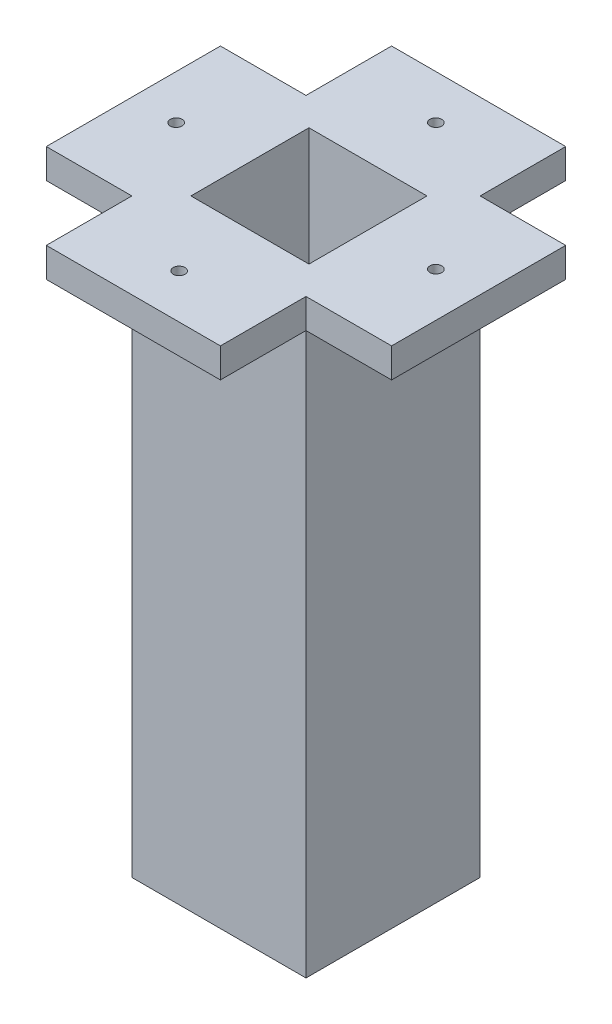
SolidWorks part; units mm, degrees
ref_plane "Plan de face" through (0, 0, 0) normal (0, 0, 1) x (1, 0, 0)
ref_plane "Plan de dessus" through (0, 0, 0) normal (0, 1, 0) x (1, 0, 0)
ref_plane "Plan de droite" through (0, 0, 0) normal (1, 0, 0) x (0, 0, -1)
sketch "Esquisse1" plane through (0, 0, 0) normal (0, 1, 0) x (1, 0, 0)
  line L1 (0, 0) -> (59, 0)
  line L2 (0, 0) -> (0, 59)
  line L3 (0, 59) -> (59, 59)
  line L4 (59, 0) -> (59, 59)
extrude "Boss.-Extru.1" add sketch "Esquisse1" along normal blind 200 contours L2 L1 L4 L3
sketch "Esquisse2" plane through (0, 200, 0) normal (0, 1, 0) x (1, 0, 0)
  line L1 (10, 50) -> (50, 50)
  line L2 (10, 50) -> (10, 10)
  line L3 (10, 10) -> (50, 10)
  line L4 (50, 50) -> (50, 10)
extrude "Enlèv. mat.-Extru.1" cut sketch "Esquisse2" against normal blind 250 contours L2 L1 L4 L3
sketch "Esquisse3" plane through (0, 0, 0) normal (1, 0, 0) x (0, 0, -1)
  line L5 (39, 120) -> (20, 120)
  line L6 (39, 120) -> (39, 79)
  line L7 (39, 79) -> (20, 79)
  line L8 (20, 120) -> (20, 79)
  line L13 (0, 200) -> (59, 200) construction
  line L14 (59, 200) -> (59, 0) construction
  line L15 (0, 71.0556) -> (0, -71.0556) construction
  dimension "D1" = 80
  dimension "D2" = 20
  dimension "D3" = 121
  dimension "D4" = 20
extrude "Enlèv. mat.-Extru.7" cut sketch "Esquisse3" along normal blind 10
sketch "Esquisse6" plane through (0, 0, 0) normal (-1, 0, 0) x (0, 0, 1)
  line L0 (-39, 120) -> (-20, 120) construction
  line L1 (-20, 120) -> (-20, 79) construction
  line L2 (-39, 79) -> (-39, 120) construction
  line L3 (-20, 79) -> (-39, 79) construction
  circle A0 centre (-33.5, 123.5) radius 2
  circle A1 centre (-25.5, 123.5) radius 2
  circle A2 centre (-33.5, 75.5) radius 2
  circle A3 centre (-25.5, 75.5) radius 2
  dimension "D1" = 3.5
  dimension "D2" = 4
  dimension "D4" = 4
  dimension "D7" = 5.5
  dimension "D11" = 4
  dimension "D12" = 4
  dimension "D3" = 5.5
  dimension "D5" = 3.5
  dimension "D6" = 5.5
  dimension "D8" = 5.5
  dimension "D9" = 3.5
  dimension "D10" = 3.5
extrude "Enlèv. mat.-Extru.8" cut sketch "Esquisse6" against normal blind 10
sketch "Esquisse14" plane through (0, 200, 0) normal (0, 1, 0) x (1, 0, 0)
  line L0 (0, -46.4511) -> (0, 46.4511) construction
  line L1 (59, 59) -> (0, 59)
  line L2 (59, 59) -> (59, 88)
  line L3 (59, 88) -> (0, 88)
  line L4 (0, 59) -> (0, 88)
  line L5 (-71.0556, 0) -> (71.0556, 0) construction
  line L6 (59, 59) -> (88, 59)
  line L7 (59, 59) -> (59, 0)
  line L8 (59, 0) -> (88, 0)
  line L9 (88, 59) -> (88, 0)
  line L11 (0, 59) -> (-29, 59)
  line L12 (0, 59) -> (0, 0)
  line L13 (0, 0) -> (-29, 0)
  line L14 (-29, 59) -> (-29, 0)
  line L15 (0, 0) -> (59, 0)
  line L16 (0, 0) -> (0, -29)
  line L17 (0, -29) -> (59, -29)
  line L18 (59, 0) -> (59, -29)
  line M9 (59, 59) -> (0, 59)
  line M10 (0, 59) -> (0, 0)
  line M11 (0, 0) -> (59, 0)
  line M12 (59, 0) -> (59, 59)
  dimension "D1" = 29
  dimension "D2" = 59
  dimension "D3" = 29
  dimension "D4" = 29
  dimension "D5" = 29
extrude "Boss.-Extru.3" add sketch "Esquisse14" against normal blind 10 contours L9 L6 L8 M12 | L18 L16 L17 M11 | L11 L14 L13 M10 | L4 L2 L3 M9
sketch "Esquisse17" plane through (0, 190, 0) normal (0, -1, 0) x (-1, 0, 0)
  line L0 (-71.0556, 0) -> (71.0556, 0) construction
  line L1 (-59, 88) -> (0, 88) construction
  line L2 (-88, 59) -> (-88, 0) construction
  line L3 (0, 46.4511) -> (0, -46.4511) construction
  line L4 (29, 59) -> (29, 0) construction
  line L5 (0, 59) -> (29, 59) construction
  line L6 (0, -29) -> (-59, -29) construction
  line L7 (0, 0) -> (0, -29) construction
  circle A0 centre (-73, 30) radius 2
  circle A1 centre (-30, -14) radius 2
  circle A2 centre (14, 29) radius 2
  circle A3 centre (-30, 73) radius 2
  point P4 (0, 0)
  point P6 (-88, 33.643)
  point P10 (-32.4962, -11.7503)
  point P13 (13.0773, 28.4192)
  point P16 (-29.0736, 70.7503)
  dimension "D1" = 4
  dimension "D2" = 30
  dimension "D3" = 15
  dimension "D4" = 15
  dimension "D5" = 30
  dimension "D6" = 15
  dimension "D7" = 30
  dimension "D8" = 15
  dimension "D9" = 30
extrude "Enlèv. mat.-Extru.9" cut sketch "Esquisse17" against normal blind 10
